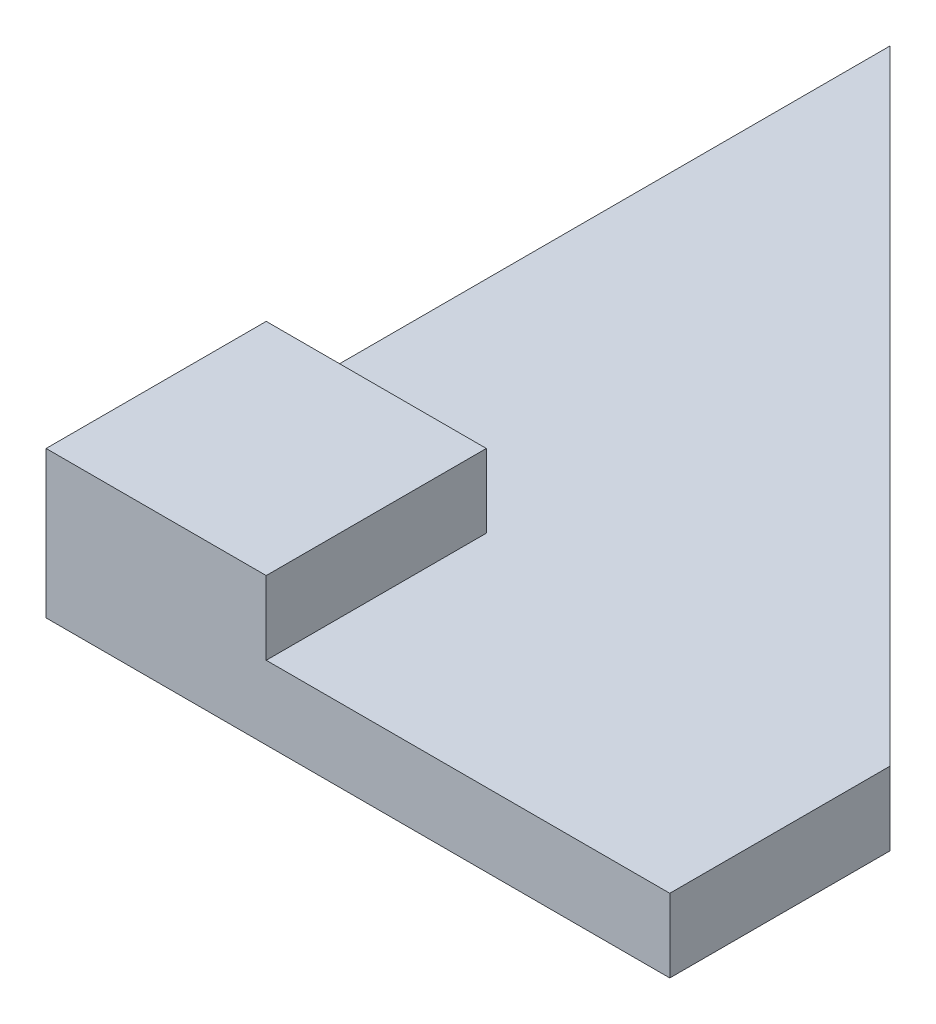
SolidWorks part; units mm, degrees
ref_plane "Front Plane" through (0, 0, 0) normal (0, 0, 1) x (1, 0, 0)
ref_plane "Top Plane" through (0, 0, 0) normal (0, 1, 0) x (1, 0, 0)
ref_plane "Right Plane" through (0, 0, 0) normal (1, 0, 0) x (0, 0, -1)
sketch "Sketch1" plane through (0, 0, 0) normal (0, 1, 0) x (1, 0, 0)
  line L1 (-15, -15) -> (15, -15)
  line L2 (-15, -15) -> (-15, 15)
  line L3 (-15, 15) -> (15, 15)
  line L4 (15, -15) -> (15, 15)
  line L5 (-15, -15) -> (15, 15) construction
  line L6 (-15, 15) -> (15, -15) construction
  point P0 (0, 0)
  dimension "D1" = 30
  dimension "D2" = 30
extrude "Boss-Extrude1" add sketch "Sketch1" along normal blind 10
sketch "Sketch3" plane through (0, 0, 0) normal (0, -1, 0) x (1, 0, 0)
  line L1 (-15, -100) -> (100, 15)
  line L2 (100, 15) -> (-15, 15)
  line L3 (-15, 15) -> (15, 15) construction
  line L4 (-15, -15) -> (-15, 15) construction
  line L6 (-15, 15) -> (-15, -100)
  line L7 (-15, -15) -> (70, -15) construction
  line L8 (70, -15) -> (70, 15)
  line M1 (15, -15) -> (15, 15)
  line M2 (15, 15) -> (-15, 15)
  line M3 (-15, 15) -> (-15, -15)
  line M4 (-15, -15) -> (15, -15)
  dimension "D1" = 85
extrude "Boss-Extrude3" add sketch "Sketch3" along normal blind 10 contours L7 L8 L2 M1 | L7 L6 L1 M4 | M4 M1 M2 M3
